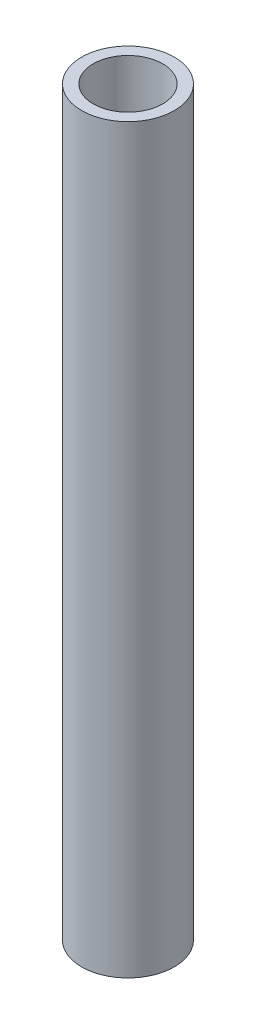
SolidWorks part; units mm, degrees
ref_plane "Front Plane" through (0, 0, 0) normal (0, 0, 1) x (1, 0, 0)
ref_plane "Top Plane" through (0, 0, 0) normal (0, 1, 0) x (1, 0, 0)
ref_plane "Right Plane" through (0, 0, 0) normal (1, 0, 0) x (0, 0, -1)
sketch "Sketch1" plane through (0, 0, 0) normal (0, 1, 0) x (1, 0, 0)
  circle A0 centre (0, 0) radius 3.175
  circle A1 centre (0, 0) radius 2.3813
extrude "Boss-Extrude1" add sketch "Sketch1" along normal blind 50.8
hole_wizard "1/8 (0.1250) Dowel Hole1" positions "3DSketch4" profile "Sketch3" hole size "1/8" standard "ANSI Inch"
sketch3d "3DSketch4"
  point P0 (-3.175, 3.175, 0.0016)
sketch "Sketch3" plane through (-3.175, 3.175, 0.0016) normal (0, 1, 0) x (0.0005, 0, 1)
  line L0 (0, 0) -> (0, 4.1339)
  line L1 (0, 4.1339) -> (1.5875, 3.18)
  line L2 (1.5875, 3.18) -> (1.5875, 0)
  line L5 (1.5875, 0) -> (0, 0)
  line L10 (0, 4.1339) -> (-1.5875, 3.18) construction
  line L11 (0, -6.35) -> (0, 107.95) construction
  dimension "Hole Dia." = 3.175
  dimension "Hole Depth" = 3.18
  dimension "Drill Angle" = 118
